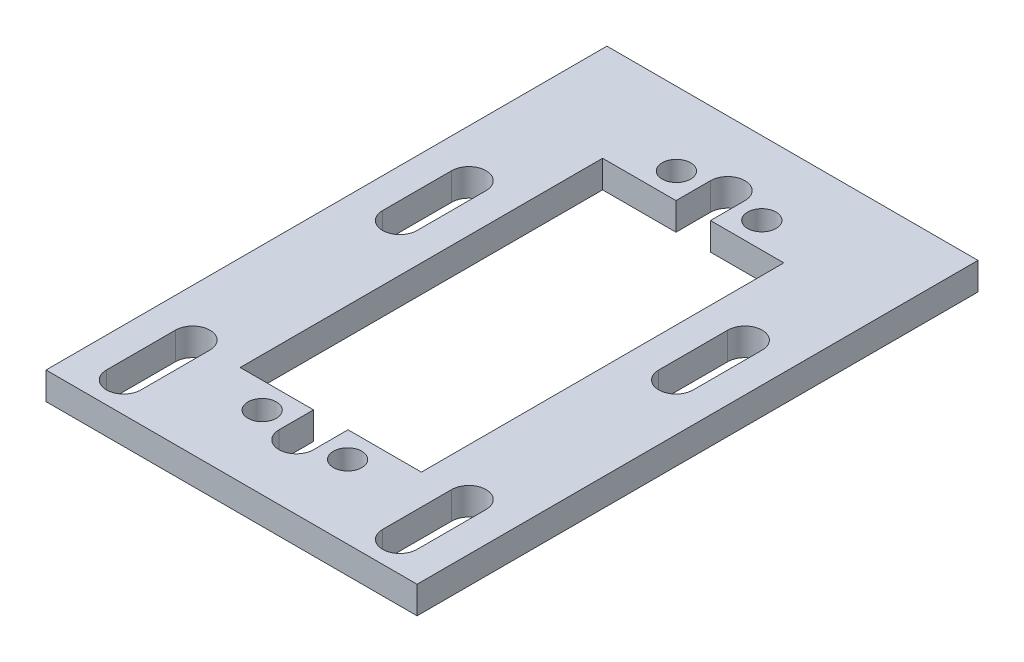
SolidWorks part; units mm, degrees
ref_plane "Front" through (0, 0, 0) normal (0, 0, 1) x (1, 0, 0)
ref_plane "Top" through (0, 0, 0) normal (0, 1, 0) x (1, 0, 0)
ref_plane "Right" through (0, 0, 0) normal (1, 0, 0) x (0, 0, -1)
sketch "Sketch1" plane through (0, 0, 0) normal (0, 1, 0) x (1, 0, 0)
  line L0 (0, 21) -> (0, 25)
  line L1 (-10.5, -21) -> (10.5, -21)
  line L2 (-10.5, -21) -> (-10.5, 21)
  line L3 (-10.5, 21) -> (10.5, 21)
  line L4 (10.5, -21) -> (10.5, 21)
  line L5 (-10.5, -21) -> (10.5, 21) construction
  line L6 (-10.5, 21) -> (10.5, -21) construction
  line L7 (-21.5, 32.5) -> (21.5, 32.5)
  line L8 (-21.5, 32.5) -> (-21.5, -32.5)
  line L9 (-21.5, -32.5) -> (21.5, -32.5)
  line L10 (21.5, 32.5) -> (21.5, -32.5)
  line L11 (-21.5, 32.5) -> (21.5, -32.5) construction
  line L12 (-21.5, -32.5) -> (21.5, 32.5) construction
  line L13 (-2, 25) -> (-2, 21)
  line L14 (2, 25) -> (2, 21)
  line L15 (0, 24) -> (0, -24)
  line L16 (-4.95, -24) -> (4.95, -24)
  line L17 (-4.95, 24) -> (4.95, 24)
  line L18 (-10.5, 0) -> (10.5, 0)
  line L19 (2, -25) -> (2, -21)
  line L20 (-2, -25) -> (-2, -21)
  arc A0 (-2, 25) -> (2, 25) centre (0, 25) cw
  circle A1 centre (4.95, 24) radius 1.65
  circle A2 centre (-4.95, 24) radius 1.65
  circle A3 centre (-4.95, -24) radius 1.65
  circle A4 centre (4.95, -24) radius 1.65
  arc A5 (-2, -25) -> (2, -25) centre (0, -25) ccw
  point P0 (0, 0)
  point P6 (0, 0)
  point P20 (0, 0)
  point P23 (0, -24)
  point P26 (0, 24)
  dimension "D5" = 2
  dimension "D4" = 4
  dimension "D9" = 43
  dimension "D1" = 21
  dimension "D2" = 42
  dimension "D3" = 65
  dimension "D6" = 9.9
  dimension "D7" = 9.9
  dimension "D8" = 48
extrude "Boss-Extrude1" add sketch "Sketch1" along normal blind 3.175
sketch "Sketch3" plane through (0, 3.175, 0) normal (0, 1, 0) x (1, 0, 0)
  line L0 (-16, -25) -> (16, -25)
  line L1 (-16, -21) -> (-16, -29) construction
  line L2 (-14, -21) -> (-14, -29)
  line L3 (-18, -21) -> (-18, -29)
  line L4 (0, 0) -> (0, -25)
  line L5 (16, -21) -> (16, -29) construction
  line L6 (14, -21) -> (14, -29)
  line L7 (18, -21) -> (18, -29)
  line L8 (-16, 11) -> (-16, 3) construction
  line L9 (-14, 11) -> (-14, 3)
  line L10 (-18, 11) -> (-18, 3)
  line L11 (16, 11) -> (16, 3) construction
  line L12 (14, 11) -> (14, 3)
  line L13 (18, 11) -> (18, 3)
  arc A0 (-14, -21) -> (-18, -21) centre (-16, -21) ccw
  arc A1 (-18, -29) -> (-14, -29) centre (-16, -29) ccw
  arc A2 (14, -21) -> (18, -21) centre (16, -21) cw
  arc A3 (18, -29) -> (14, -29) centre (16, -29) cw
  arc A4 (-14, 11) -> (-18, 11) centre (-16, 11) ccw
  arc A5 (-18, 3) -> (-14, 3) centre (-16, 3) ccw
  arc A6 (14, 11) -> (18, 11) centre (16, 11) cw
  arc A7 (18, 3) -> (14, 3) centre (16, 3) cw
  point P3 (0, -25)
  point P6 (-16, -25)
  point P15 (16, -25)
  point P24 (-16, 7)
  point P31 (16, 7)
  dimension "D3" = 2
  dimension "D1" = 32
  dimension "D2" = 0
  dimension "D4" = 25
  dimension "D5" = 8
  dimension "D6" = 2
extrude "Cut-Extrude1" cut sketch "Sketch3" against normal blind 3.175
